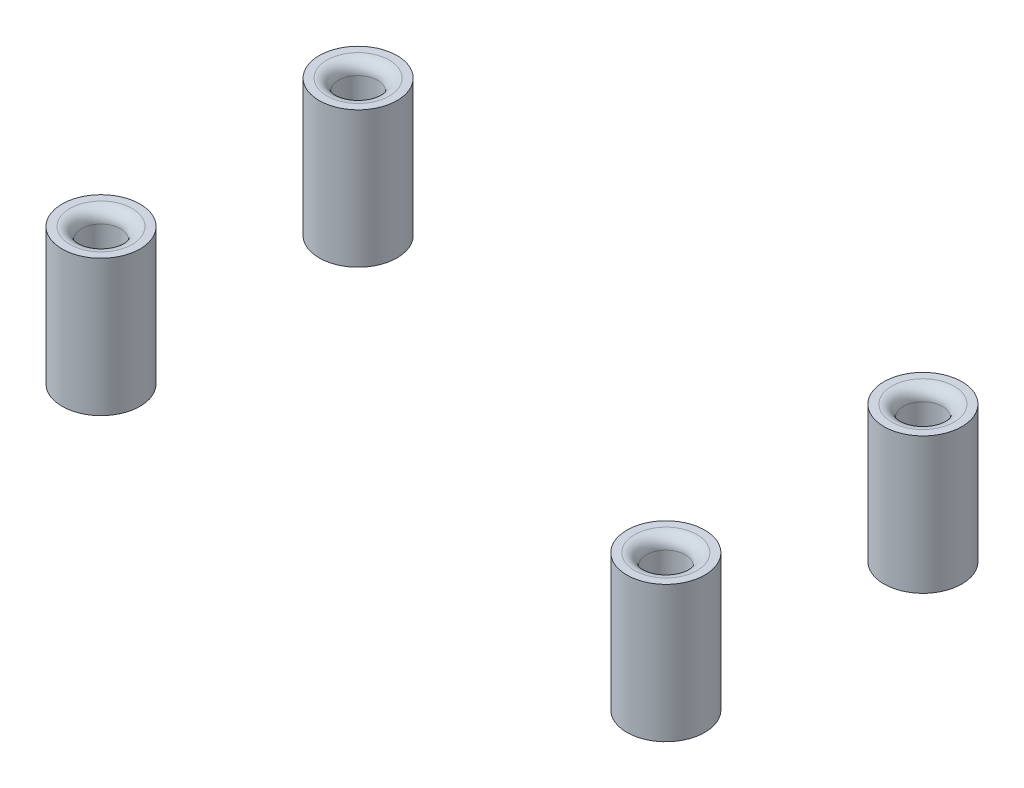
SolidWorks part; units mm, degrees
ref_plane "Front Plane" through (0, 0, 0) normal (0, 0, 1) x (1, 0, 0)
ref_plane "Top Plane" through (0, 0, 0) normal (0, 1, 0) x (1, 0, 0)
ref_plane "Right Plane" through (0, 0, 0) normal (1, 0, 0) x (0, 0, -1)
sketch "Sketch1" plane through (0, 0, 0) normal (0, 1, 0) x (1, 0, 0)
  line L1 (-82.5, 43) -> (82.5, 43)
  line L2 (-82.5, 43) -> (-82.5, -43)
  line L3 (-82.5, -43) -> (82.5, -43)
  line L4 (82.5, 43) -> (82.5, -43)
  line L5 (-82.5, 43) -> (82.5, -43) construction
  line L6 (-82.5, -43) -> (82.5, 43) construction
  circle A0 centre (-72.5, -33) radius 10
  circle A1 centre (-72.5, 33) radius 10
  circle A2 centre (72.5, 33) radius 10
  circle A3 centre (72.5, -33) radius 10
  circle A4 centre (-72.5, -33) radius 5
  circle A5 centre (-72.5, 33) radius 5
  circle A6 centre (72.5, 33) radius 5
  circle A7 centre (72.5, -33) radius 5
  point P0 (0, 0)
  dimension "D3" = 20
  dimension "D4" = 10
  dimension "D1" = 165
  dimension "D2" = 86
extrude "Boss-Extrude1" add sketch "Sketch1" along normal blind 35 contours A0 A4 | A1 A5 | A3 A7 | A2 A6
fillet "Fillet2" radius 3 1 edges at (72.5, 35, -28)
fillet "Fillet3" radius 3 1 edges at (-72.5, 35, -28)
fillet "Fillet4" radius 3 1 edges at (-72.5, 35, 38)
fillet "Fillet5" radius 3 1 edges at (72.5, 35, 38)
